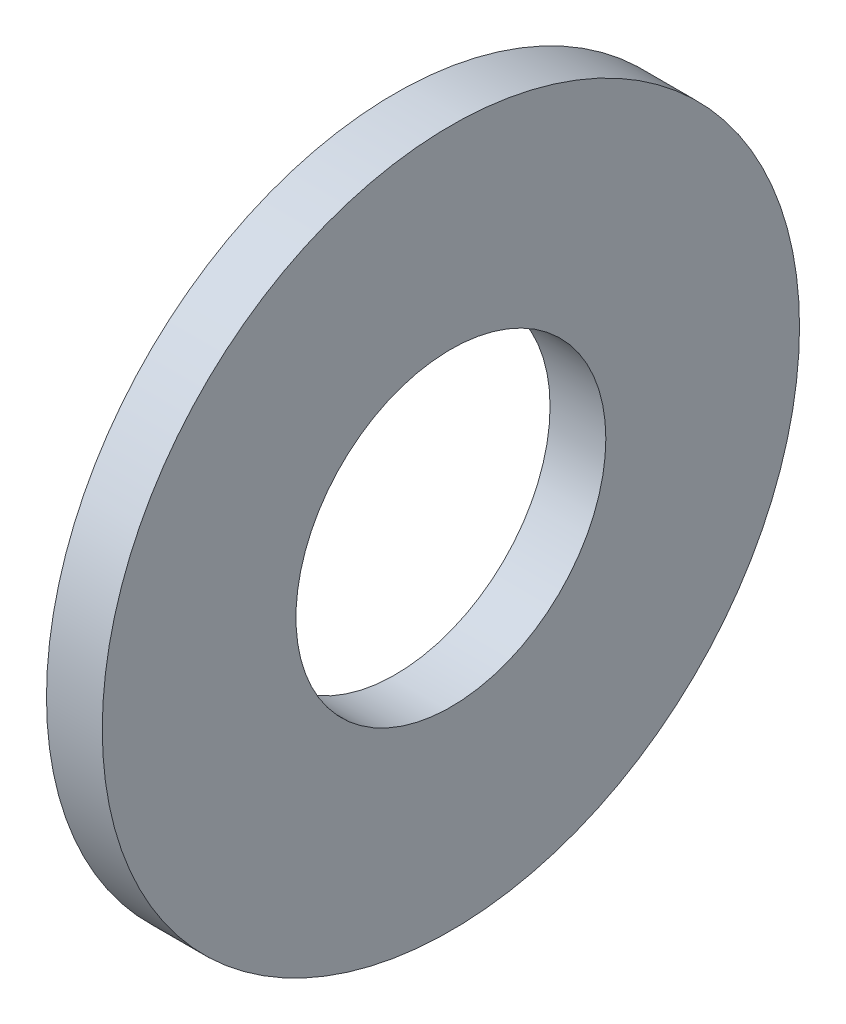
SolidWorks part; units mm, degrees
ref_plane "Front Plane" through (0, 0, 0) normal (0, 0, 1) x (1, 0, 0)
ref_plane "Top Plane" through (0, 0, 0) normal (0, 1, 0) x (1, 0, 0)
ref_plane "Right Plane" through (0, 0, 0) normal (1, 0, 0) x (0, 0, -1)
sketch "Sketch1" plane through (0, 0, 0) normal (1, 0, 0) x (0, 0, -1)
  circle A0 centre (0, 0) radius 5.715
  circle A1 centre (0, 0) radius 2.54
  dimension "OD" = 11.43
  dimension "ID" = 5.08
extrude "Boss-Extrude1" add sketch "Sketch1" along normal blind 0.9144
